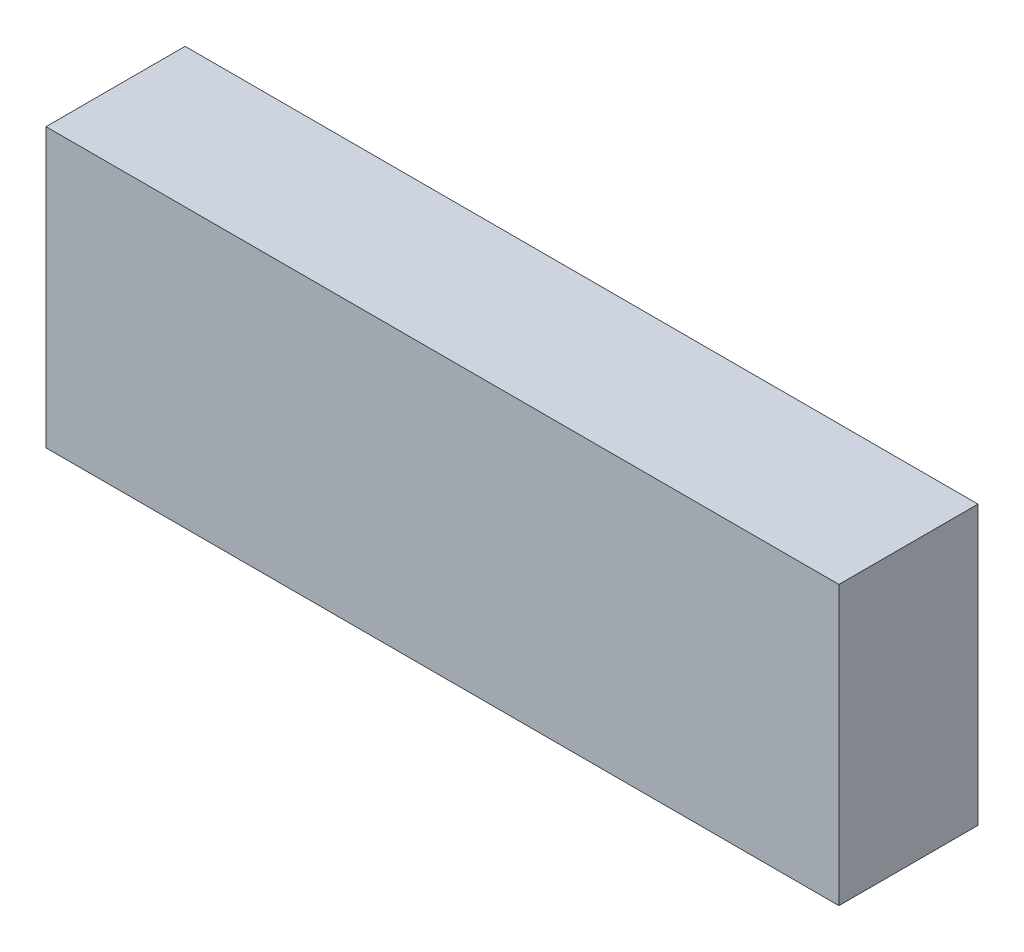
SolidWorks part; units mm, degrees
ref_plane "Front Plane" through (0, 0, 0) normal (0, 0, 1) x (1, 0, 0)
ref_plane "Top Plane" through (0, 0, 0) normal (0, 1, 0) x (1, 0, 0)
ref_plane "Right Plane" through (0, 0, 0) normal (1, 0, 0) x (0, 0, -1)
sketch "Sketch1" plane through (0, 0, 0) normal (0, 0, 1) x (1, 0, 0)
  line L1 (0, 0) -> (57, 0)
  line L2 (0, 0) -> (0, 20)
  line L3 (0, 20) -> (57, 20)
  line L4 (57, 0) -> (57, 20)
extrude "Boss-Extrude1" add sketch "Sketch1" along normal blind 10
